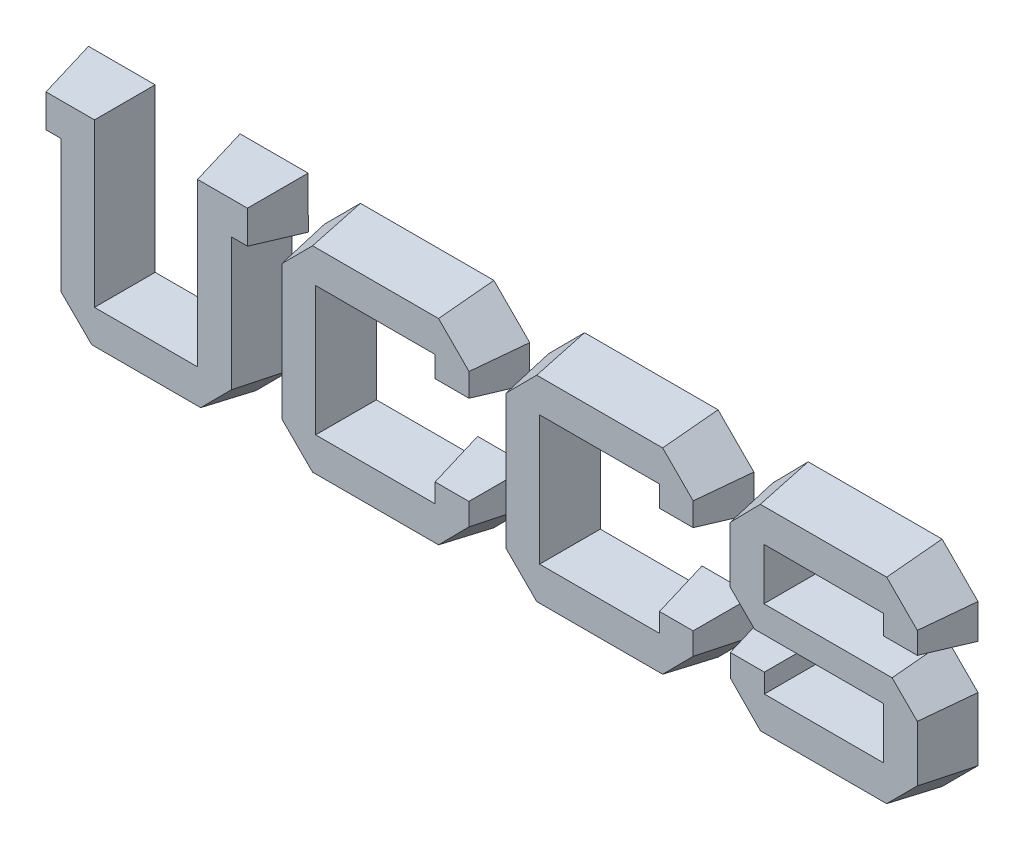
SolidWorks part; units mm, degrees
ref_plane "Front Plane" through (0, 0, 0) normal (0, 0, 1) x (1, 0, 0)
ref_plane "Top Plane" through (0, 0, 0) normal (0, 1, 0) x (1, 0, 0)
ref_plane "Right Plane" through (0, 0, 0) normal (1, 0, 0) x (0, 0, -1)
sketch "Sketch2" plane through (0, 0, 0) normal (0, 0, 1) x (1, 0, 0)
  line L0 (67.8425, 25.0268) -> (57.4595, 25.0201)
  line L1 (57.4595, 25.0201) -> (54.7108, 22.2244)
  line L2 (54.7108, 22.2244) -> (54.7108, 17.2984)
  line L3 (54.7108, 17.2984) -> (57.0159, 15)
  line L4 (57.0159, 15) -> (66.5925, 15.0067)
  line L5 (66.5925, 15.0067) -> (66.5925, 12.4395)
  line L6 (66.5925, 12.4395) -> (58.77, 12.4395)
  line L7 (58.77, 12.4395) -> (58.77, 13.9113)
  line L8 (58.77, 13.9113) -> (54.7176, 13.9113)
  line L9 (54.7176, 13.9113) -> (54.7176, 11.203)
  line L10 (54.7176, 11.203) -> (57.4662, 8.4073)
  line L11 (57.4662, 8.4073) -> (67.8358, 8.4073)
  line L12 (67.8358, 8.4073) -> (70.6248, 11.203)
  line L13 (70.6248, 11.203) -> (70.6248, 16.1156)
  line L14 (70.6248, 16.1156) -> (68.2592, 18.4812)
  line L15 (68.2592, 18.4812) -> (58.7364, 18.4812)
  line L16 (58.7364, 18.4812) -> (58.7364, 21.0618)
  line L17 (58.7364, 21.0618) -> (66.5858, 21.0618)
  line L18 (66.5858, 21.0618) -> (66.5858, 19.5497)
  line L19 (66.5858, 19.5497) -> (70.6248, 19.5497)
  line L20 (70.6248, 19.5497) -> (70.6248, 22.2244)
  line L21 (70.6248, 22.2244) -> (67.8425, 25.0268)
  line L22 (50.477, 25.0201) -> (40.1276, 25.0201)
  line L23 (40.1276, 25.0201) -> (37.3453, 22.2244)
  line L24 (37.3453, 22.2244) -> (37.3386, 11.203)
  line L25 (37.3386, 11.203) -> (40.1276, 8.414)
  line L26 (40.1276, 8.414) -> (50.477, 8.414)
  line L27 (50.477, 8.414) -> (53.2458, 11.2097)
  line L28 (53.2458, 11.2097) -> (53.2458, 13.918)
  line L29 (53.2458, 13.918) -> (49.2337, 13.918)
  line L30 (49.2337, 13.918) -> (49.2337, 12.4463)
  line L31 (49.2337, 12.4463) -> (41.3507, 12.4463)
  line L32 (41.3507, 12.4463) -> (41.3507, 21.0618)
  line L33 (41.3507, 21.0618) -> (49.2337, 21.0618)
  line L34 (49.2337, 21.0618) -> (49.2337, 19.4355)
  line L35 (49.2337, 19.4355) -> (53.2525, 19.4355)
  line L36 (53.2525, 19.4355) -> (53.2525, 22.2312)
  line L37 (53.2525, 22.2312) -> (50.477, 25.0201)
  line L38 (33.1047, 25.0201) -> (22.7553, 25.0201)
  line L39 (22.7553, 25.0201) -> (19.9663, 22.2244)
  line L40 (19.9663, 22.2244) -> (19.9596, 11.203)
  line L41 (19.9596, 11.203) -> (22.7553, 8.414)
  line L42 (22.7553, 8.414) -> (33.1047, 8.414)
  line L43 (33.1047, 8.414) -> (35.8668, 11.2097)
  line L44 (35.8668, 11.2097) -> (35.8668, 13.918)
  line L45 (35.8668, 13.918) -> (31.8413, 13.918)
  line L46 (31.8413, 13.918) -> (31.8413, 12.4463)
  line L47 (31.8413, 12.4463) -> (23.9918, 12.4463)
  line L48 (23.9918, 12.4463) -> (23.9918, 21.0618)
  line L49 (23.9918, 21.0618) -> (31.8413, 21.0618)
  line L50 (31.8413, 21.0618) -> (31.8413, 19.4355)
  line L51 (31.8413, 19.4355) -> (35.8735, 19.4355)
  line L52 (35.8735, 19.4355) -> (35.8803, 22.2312)
  line L53 (35.8803, 22.2312) -> (33.1047, 25.0201)
  line L54 (18.7029, 25.0201) -> (13.4274, 25.0201)
  line L55 (13.4274, 25.0201) -> (13.4274, 12.4328)
  line L56 (13.4274, 12.4328) -> (6.8481, 12.4328)
  line L57 (6.8481, 12.4328) -> (6.8481, 25.0201)
  line L58 (6.8481, 25.0201) -> (1.6801, 25.0201)
  line L59 (1.6801, 25.0201) -> (1.6801, 21.0618)
  line L60 (1.6801, 21.0618) -> (2.8293, 21.0618)
  line L61 (2.8293, 21.0618) -> (2.8293, 11.1963)
  line L62 (2.8293, 11.1963) -> (5.6452, 8.4073)
  line L63 (5.6452, 8.4073) -> (14.6707, 8.4073)
  line L64 (14.6707, 8.4073) -> (17.4596, 11.2097)
  line L65 (17.4596, 11.2097) -> (17.4596, 21.0618)
  line L66 (17.4596, 21.0618) -> (18.7163, 21.0618)
  line L67 (18.7163, 21.0618) -> (18.7029, 25.0201)
extrude "Boss-Extrude1" add sketch "Sketch2" along normal blind 4 draft 10
sketch "Sketch5" plane through (0, 0, 0) normal (0, 0, -1) x (-1, 0, 0)
  circle A0 centre (-62.8934, 23.0009) radius 1 construction
  circle A1 centre (-62.8934, 10.3957) radius 1 construction
  circle A2 centre (-45.5801, 10.3957) radius 1 construction
  circle A3 centre (-45.5801, 23.0009) radius 1 construction
  circle A4 centre (-28.1801, 10.3957) radius 1 construction
  circle A5 centre (-28.1801, 23.0009) radius 1 construction
  circle A6 centre (-15.3921, 16.6642) radius 1 construction
  circle A7 centre (-4.8593, 16.6642) radius 1 construction
  circle A8 centre (-62.8934, 23.0009) radius 1 construction
  circle A9 centre (-62.8934, 10.3957) radius 1 construction
  circle A10 centre (-45.5801, 10.3957) radius 1 construction
  circle A11 centre (-45.5801, 23.0009) radius 1 construction
  circle A12 centre (-28.1801, 10.3957) radius 1 construction
  circle A13 centre (-28.1801, 23.0009) radius 1 construction
  circle A14 centre (-15.3921, 16.6642) radius 1 construction
  circle A15 centre (-4.8593, 16.6642) radius 1 construction
  circle A16 centre (-62.8934, 23.0009) radius 1.127
  circle A17 centre (-62.8934, 10.3957) radius 1.127
  circle A18 centre (-45.5801, 10.3957) radius 1.127
  circle A19 centre (-45.5801, 23.0009) radius 1.127
  circle A20 centre (-28.1801, 10.3957) radius 1.127
  circle A21 centre (-28.1801, 23.0009) radius 1.127
  circle A22 centre (-15.3921, 16.6642) radius 1.127
  circle A23 centre (-4.8593, 16.6642) radius 1.127
  dimension "D1" = 0.127
extrude "Cut-Extrude1" cut sketch "Sketch5" against normal blind 2.01
